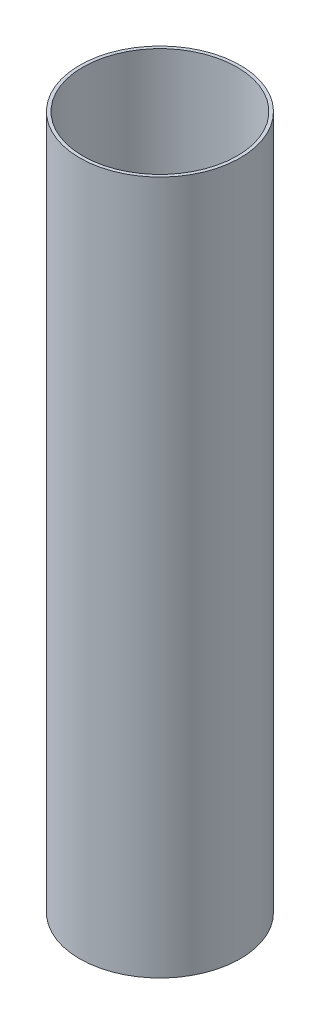
SolidWorks part; units mm, degrees
ref_plane "Front" through (0, 0, 0) normal (0, 0, 1) x (1, 0, 0)
ref_plane "Top" through (0, 0, 0) normal (0, 1, 0) x (1, 0, 0)
ref_plane "Right" through (0, 0, 0) normal (1, 0, 0) x (0, 0, -1)
sketch "Sketch1" plane through (0, 0, 0) normal (0, 1, 0) x (1, 0, 0)
  circle A0 centre (0, 0) radius 76.2
  circle A1 centre (0, 0) radius 79.375
  dimension "D1" = 152.4
  dimension "D2" = 3.175
extrude "Boss-Extrude1" add sketch "Sketch1" along normal blind 685.8
